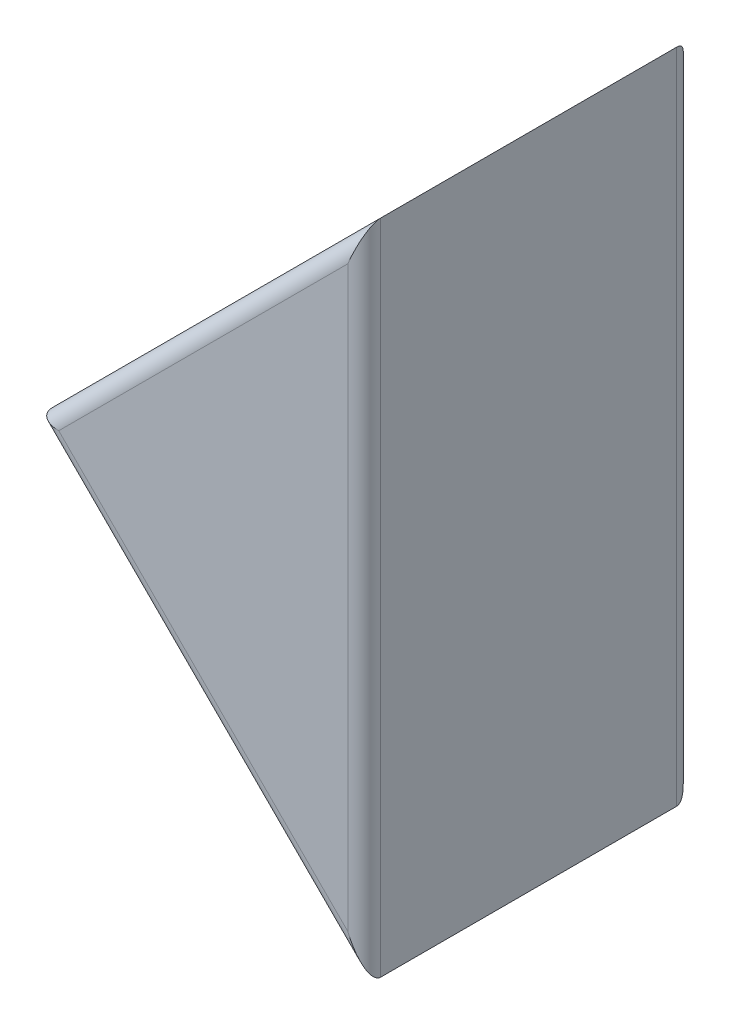
SolidWorks part; units mm, degrees
material "PVC 0.007 Plasticized"
ref_plane "Front Plane" through (0, 0, 0) normal (0, 0, 1) x (1, 0, 0)
ref_plane "Top Plane" through (0, 0, 0) normal (0, 1, 0) x (1, 0, 0)
ref_plane "Right Plane" through (0, 0, 0) normal (1, 0, 0) x (0, 0, -1)
sketch "Sketch1" plane through (0, 0, 0) normal (0, 1, 0) x (1, 0, 0)
  line L1 (-10, -10) -> (10, -10)
  line L2 (-10, -10) -> (-10, 10)
  line L3 (-10, 10) -> (10, 10)
  line L4 (10, -10) -> (10, 10)
  line L5 (-10, -10) -> (10, 10) construction
  line L6 (-10, 10) -> (10, -10) construction
  point P0 (0, 0)
  dimension "D1" = 20
  dimension "D2" = 20
extrude "Boss-Extrude1" add sketch "Sketch1" along normal blind 40
sketch "Sketch2" plane through (0, 0, 10) normal (0, 0, 1) x (1, 0, 0)
  line L0 (10, 40) -> (-10, 20)
  line L1 (-10, 40) -> (-10, 0) construction
  line L2 (-10, 20) -> (10, 0)
  line L3 (10, 40) -> (-10, 40)
  line L4 (-10, 40) -> (-10, 20)
  line L5 (-10, 20) -> (-10, 0)
  line L6 (-10, 0) -> (10, 0)
  line M1 (-10, 0) -> (10, 0)
  line M3 (10, 40) -> (-10, 40)
  line M4 (-10, 40) -> (-10, 0)
extrude "Cut-Extrude1" cut sketch "Sketch2" against normal through all contours L0 M3 M4 | L2 M4 M1
fillet "Fillet1" radius 1 6 edges at (0, 30, 10) (10, 20, 10) (0, 10, 10) (10, 20, -10) (0, 30, -10) (0, 10, -10)
